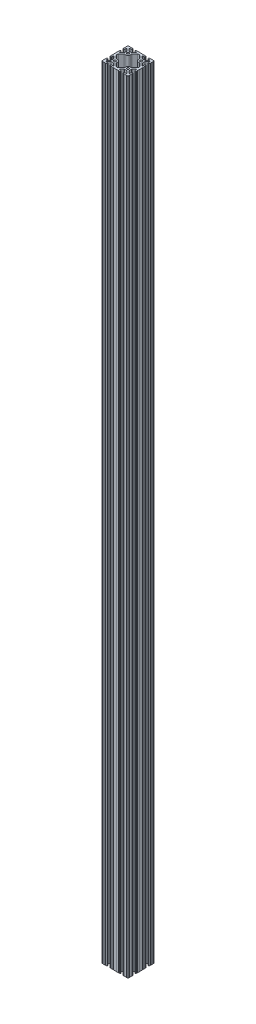
SolidWorks part; units mm, degrees
ref_plane "Piano frontale" through (0, 0, 0) normal (0, 0, 1) x (1, 0, 0)
ref_plane "Piano superiore" through (0, 0, 0) normal (0, 1, 0) x (1, 0, 0)
ref_plane "Piano destro" through (0, 0, 0) normal (1, 0, 0) x (0, 0, -1)
ref_plane "Piano1" through (0, 0, 0) normal (0, -1, 0) x (1, 0, 0)
sketch "Schizzo1" plane through (0, 0, 0) normal (0, -1, 0) x (1, 0, 0)
  line L0 (16.5037, -39.4963) -> (13.5247, -39.4963)
  line L1 (12.1105, -38.9105) -> (6.0284, -32.8284)
  line L2 (6.0284, -27.1716) -> (12.1105, -21.0895)
  line L3 (13.5247, -20.5037) -> (16.5037, -20.5037)
  line L4 (20.5037, -16.5037) -> (20.5037, -13.5247)
  line L5 (21.0895, -12.1105) -> (27.1716, -6.0284)
  line L6 (32.8284, -6.0284) -> (38.9105, -12.1105)
  line L7 (39.4963, -13.5247) -> (39.4963, -16.5037)
  line L8 (43.4963, -20.5037) -> (46.4753, -20.5037)
  line L9 (47.8895, -21.0895) -> (53.9716, -27.1716)
  line L10 (53.9716, -32.8284) -> (47.8895, -38.9105)
  line L11 (46.4753, -39.4963) -> (43.4963, -39.4963)
  line L12 (39.4963, -43.4963) -> (39.4963, -46.4753)
  line L13 (38.9105, -47.8895) -> (32.8284, -53.9716)
  line L14 (27.1716, -53.9716) -> (21.0895, -47.8895)
  line L15 (20.5037, -46.4753) -> (20.5037, -43.4963)
  line L16 (10.4, 0) -> (8.4, 0)
  line L17 (7.6, 0) -> (3, 0)
  line L18 (2.2, 0) -> (2, 0)
  line L19 (0, -2) -> (0, -2.2)
  line L20 (0, -3) -> (0, -7.6)
  line L21 (0, -8.4) -> (0, -10.4)
  line L22 (1.4, -11.8) -> (1.8, -11.8)
  line L23 (3.2, -10.4) -> (3.2, -7.3541)
  line L24 (4.5657, -6.7884) -> (8.9542, -11.177)
  line L25 (9.54, -12.5912) -> (9.54, -17.3716)
  line L26 (8.9542, -18.7858) -> (4.5657, -23.1743)
  line L27 (3.2, -22.6086) -> (3.2, -19.6)
  line L28 (1.8, -18.2) -> (1.4, -18.2)
  line L29 (0, -19.6) -> (0, -20.4)
  line L30 (0, -21.2) -> (0, -25.8)
  line L31 (0, -26.6) -> (0, -33.4)
  line L32 (0, -34.2) -> (0, -38.8)
  line L33 (0, -39.6) -> (0, -40.4)
  line L34 (1.4, -41.8) -> (1.8, -41.8)
  line L35 (3.2, -40.4) -> (3.2, -37.3914)
  line L36 (4.5657, -36.8257) -> (8.9542, -41.2142)
  line L37 (9.54, -42.6284) -> (9.54, -47.4088)
  line L38 (8.9542, -48.823) -> (4.5657, -53.2116)
  line L39 (3.2, -52.6459) -> (3.2, -49.6)
  line L40 (1.8, -48.2) -> (1.4, -48.2)
  line L41 (0, -49.6) -> (0, -51.6)
  line L42 (0, -52.4) -> (0, -57)
  line L43 (0, -57.8) -> (0, -58)
  line L44 (2, -60) -> (2.2, -60)
  line L45 (3, -60) -> (7.6, -60)
  line L46 (8.4, -60) -> (10.4, -60)
  line L47 (11.8, -58.6) -> (11.8, -58.2)
  line L48 (10.4, -56.8) -> (7.3541, -56.8)
  line L49 (6.7884, -55.4343) -> (11.177, -51.0458)
  line L50 (12.5912, -50.46) -> (17.3716, -50.46)
  line L51 (18.7858, -51.0458) -> (23.1743, -55.4343)
  line L52 (22.6086, -56.8) -> (19.6, -56.8)
  line L53 (18.2, -58.2) -> (18.2, -58.6)
  line L54 (19.6, -60) -> (20.4, -60)
  line L55 (21.2, -60) -> (25.8, -60)
  line L56 (26.6, -60) -> (33.4, -60)
  line L57 (34.2, -60) -> (38.8, -60)
  line L58 (39.6, -60) -> (40.4, -60)
  line L59 (41.8, -58.6) -> (41.8, -58.2)
  line L60 (40.4, -56.8) -> (37.3914, -56.8)
  line L61 (36.8257, -55.4343) -> (41.2142, -51.0458)
  line L62 (42.6284, -50.46) -> (47.4088, -50.46)
  line L63 (48.823, -51.0458) -> (53.2116, -55.4343)
  line L64 (52.6459, -56.8) -> (49.6, -56.8)
  line L65 (48.2, -58.2) -> (48.2, -58.6)
  line L66 (49.6, -60) -> (51.6, -60)
  line L67 (52.4, -60) -> (57, -60)
  line L68 (57.8, -60) -> (58, -60)
  line L69 (60, -58) -> (60, -57.8)
  line L70 (60, -57) -> (60, -52.4)
  line L71 (60, -51.6) -> (60, -49.6)
  line L72 (58.6, -48.2) -> (58.2, -48.2)
  line L73 (56.8, -49.6) -> (56.8, -52.6459)
  line L74 (55.4343, -53.2116) -> (51.0458, -48.823)
  line L75 (50.46, -47.4088) -> (50.46, -42.6284)
  line L76 (51.0458, -41.2142) -> (55.4343, -36.8257)
  line L77 (56.8, -37.3914) -> (56.8, -40.4)
  line L78 (58.2, -41.8) -> (58.6, -41.8)
  line L79 (60, -40.4) -> (60, -39.6)
  line L80 (60, -38.8) -> (60, -34.2)
  line L81 (60, -33.4) -> (60, -26.6)
  line L82 (60, -25.8) -> (60, -21.2)
  line L83 (60, -20.4) -> (60, -19.6)
  line L84 (58.6, -18.2) -> (58.2, -18.2)
  line L85 (56.8, -19.6) -> (56.8, -22.6086)
  line L86 (55.4343, -23.1743) -> (51.0458, -18.7858)
  line L87 (50.46, -17.3716) -> (50.46, -12.5912)
  line L88 (51.0458, -11.177) -> (55.4343, -6.7884)
  line L89 (56.8, -7.3541) -> (56.8, -10.4)
  line L90 (58.2, -11.8) -> (58.6, -11.8)
  line L91 (60, -10.4) -> (60, -8.4)
  line L92 (60, -7.6) -> (60, -3)
  line L93 (60, -2.2) -> (60, -2)
  line L94 (58, 0) -> (57.8, 0)
  line L95 (57, 0) -> (52.4, 0)
  line L96 (51.6, 0) -> (49.6, 0)
  line L97 (48.2, -1.4) -> (48.2, -1.8)
  line L98 (49.6, -3.2) -> (52.6459, -3.2)
  line L99 (53.2116, -4.5657) -> (48.823, -8.9542)
  line L100 (47.4088, -9.54) -> (42.6284, -9.54)
  line L101 (41.2142, -8.9542) -> (36.8257, -4.5657)
  line L102 (37.3914, -3.2) -> (40.4, -3.2)
  line L103 (41.8, -1.8) -> (41.8, -1.4)
  line L104 (40.4, 0) -> (39.6, 0)
  line L105 (38.8, 0) -> (34.2, 0)
  line L106 (33.4, 0) -> (26.6, 0)
  line L107 (25.8, 0) -> (21.2, 0)
  line L108 (20.4, 0) -> (19.6, 0)
  line L109 (18.2, -1.4) -> (18.2, -1.8)
  line L110 (19.6, -3.2) -> (22.6086, -3.2)
  line L111 (23.1743, -4.5657) -> (18.7858, -8.9542)
  line L112 (17.3716, -9.54) -> (12.5912, -9.54)
  line L113 (11.177, -8.9542) -> (6.7884, -4.5657)
  line L114 (7.3541, -3.2) -> (10.4, -3.2)
  line L115 (11.8, -1.8) -> (11.8, -1.4)
  arc A0 (13.5247, -39.4963) -> (12.1105, -38.9105) centre (13.5247, -37.4963) cw
  arc A1 (6.0284, -32.8284) -> (6.0284, -27.1716) centre (8.8569, -30) cw
  arc A2 (12.1105, -21.0895) -> (13.5247, -20.5037) centre (13.5247, -22.5037) cw
  arc A3 (16.5037, -20.5037) -> (20.5037, -16.5037) centre (16.5037, -16.5037) ccw
  arc A4 (20.5037, -13.5247) -> (21.0895, -12.1105) centre (22.5037, -13.5247) cw
  arc A5 (27.1716, -6.0284) -> (32.8284, -6.0284) centre (30, -8.8569) cw
  arc A6 (38.9105, -12.1105) -> (39.4963, -13.5247) centre (37.4963, -13.5247) cw
  arc A7 (39.4963, -16.5037) -> (43.4963, -20.5037) centre (43.4963, -16.5037) ccw
  arc A8 (46.4753, -20.5037) -> (47.8895, -21.0895) centre (46.4753, -22.5037) cw
  arc A9 (53.9716, -27.1716) -> (53.9716, -32.8284) centre (51.1431, -30) cw
  arc A10 (47.8895, -38.9105) -> (46.4753, -39.4963) centre (46.4753, -37.4963) cw
  arc A11 (43.4963, -39.4963) -> (39.4963, -43.4963) centre (43.4963, -43.4963) ccw
  arc A12 (39.4963, -46.4753) -> (38.9105, -47.8895) centre (37.4963, -46.4753) cw
  arc A13 (32.8284, -53.9716) -> (27.1716, -53.9716) centre (30, -51.1431) cw
  arc A14 (21.0895, -47.8895) -> (20.5037, -46.4753) centre (22.5037, -46.4753) cw
  arc A15 (20.5037, -43.4963) -> (16.5037, -39.4963) centre (16.5037, -43.4963) ccw
  circle A16 centre (15.0037, -15.0037) radius 2.62
  circle A17 centre (44.9963, -15.0037) radius 2.62
  circle A18 centre (44.9963, -44.9963) radius 2.62
  circle A19 centre (15.0037, -44.9963) radius 2.62
  arc A20 (11.8, -1.4) -> (10.4, 0) centre (10.4, -1.4) ccw
  arc A21 (8.4, 0) -> (7.6, 0) centre (8, 0) cw
  arc A22 (3, 0) -> (2.2, 0) centre (2.6, 0) cw
  arc A23 (2, 0) -> (0, -2) centre (2, -2) ccw
  arc A24 (0, -2.2) -> (0, -3) centre (0, -2.6) cw
  arc A25 (0, -7.6) -> (0, -8.4) centre (0, -8) cw
  arc A26 (0, -10.4) -> (1.4, -11.8) centre (1.4, -10.4) ccw
  arc A27 (1.8, -11.8) -> (3.2, -10.4) centre (1.8, -10.4) ccw
  arc A28 (3.2, -7.3541) -> (4.5657, -6.7884) centre (4, -7.3541) cw
  arc A29 (8.9542, -11.177) -> (9.54, -12.5912) centre (7.54, -12.5912) cw
  arc A30 (9.54, -17.3716) -> (8.9542, -18.7858) centre (7.54, -17.3716) cw
  arc A31 (4.5657, -23.1743) -> (3.2, -22.6086) centre (4, -22.6086) cw
  arc A32 (3.2, -19.6) -> (1.8, -18.2) centre (1.8, -19.6) ccw
  arc A33 (1.4, -18.2) -> (0, -19.6) centre (1.4, -19.6) ccw
  arc A34 (0, -20.4) -> (0, -21.2) centre (0, -20.8) cw
  arc A35 (0, -25.8) -> (0, -26.6) centre (0, -26.2) cw
  arc A36 (0, -33.4) -> (0, -34.2) centre (0, -33.8) cw
  arc A37 (0, -38.8) -> (0, -39.6) centre (0, -39.2) cw
  arc A38 (0, -40.4) -> (1.4, -41.8) centre (1.4, -40.4) ccw
  arc A39 (1.8, -41.8) -> (3.2, -40.4) centre (1.8, -40.4) ccw
  arc A40 (3.2, -37.3914) -> (4.5657, -36.8257) centre (4, -37.3914) cw
  arc A41 (8.9542, -41.2142) -> (9.54, -42.6284) centre (7.54, -42.6284) cw
  arc A42 (9.54, -47.4088) -> (8.9542, -48.823) centre (7.54, -47.4088) cw
  arc A43 (4.5657, -53.2116) -> (3.2, -52.6459) centre (4, -52.6459) cw
  arc A44 (3.2, -49.6) -> (1.8, -48.2) centre (1.8, -49.6) ccw
  arc A45 (1.4, -48.2) -> (0, -49.6) centre (1.4, -49.6) ccw
  arc A46 (0, -51.6) -> (0, -52.4) centre (0, -52) cw
  arc A47 (0, -57) -> (0, -57.8) centre (0, -57.4) cw
  arc A48 (0, -58) -> (2, -60) centre (2, -58) ccw
  arc A49 (2.2, -60) -> (3, -60) centre (2.6, -60) cw
  arc A50 (7.6, -60) -> (8.4, -60) centre (8, -60) cw
  arc A51 (10.4, -60) -> (11.8, -58.6) centre (10.4, -58.6) ccw
  arc A52 (11.8, -58.2) -> (10.4, -56.8) centre (10.4, -58.2) ccw
  arc A53 (7.3541, -56.8) -> (6.7884, -55.4343) centre (7.3541, -56) cw
  arc A54 (11.177, -51.0458) -> (12.5912, -50.46) centre (12.5912, -52.46) cw
  arc A55 (17.3716, -50.46) -> (18.7858, -51.0458) centre (17.3716, -52.46) cw
  arc A56 (23.1743, -55.4343) -> (22.6086, -56.8) centre (22.6086, -56) cw
  arc A57 (19.6, -56.8) -> (18.2, -58.2) centre (19.6, -58.2) ccw
  arc A58 (18.2, -58.6) -> (19.6, -60) centre (19.6, -58.6) ccw
  arc A59 (20.4, -60) -> (21.2, -60) centre (20.8, -60) cw
  arc A60 (25.8, -60) -> (26.6, -60) centre (26.2, -60) cw
  arc A61 (33.4, -60) -> (34.2, -60) centre (33.8, -60) cw
  arc A62 (38.8, -60) -> (39.6, -60) centre (39.2, -60) cw
  arc A63 (40.4, -60) -> (41.8, -58.6) centre (40.4, -58.6) ccw
  arc A64 (41.8, -58.2) -> (40.4, -56.8) centre (40.4, -58.2) ccw
  arc A65 (37.3914, -56.8) -> (36.8257, -55.4343) centre (37.3914, -56) cw
  arc A66 (41.2142, -51.0458) -> (42.6284, -50.46) centre (42.6284, -52.46) cw
  arc A67 (47.4088, -50.46) -> (48.823, -51.0458) centre (47.4088, -52.46) cw
  arc A68 (53.2116, -55.4343) -> (52.6459, -56.8) centre (52.6459, -56) cw
  arc A69 (49.6, -56.8) -> (48.2, -58.2) centre (49.6, -58.2) ccw
  arc A70 (48.2, -58.6) -> (49.6, -60) centre (49.6, -58.6) ccw
  arc A71 (51.6, -60) -> (52.4, -60) centre (52, -60) cw
  arc A72 (57, -60) -> (57.8, -60) centre (57.4, -60) cw
  arc A73 (58, -60) -> (60, -58) centre (58, -58) ccw
  arc A74 (60, -57.8) -> (60, -57) centre (60, -57.4) cw
  arc A75 (60, -52.4) -> (60, -51.6) centre (60, -52) cw
  arc A76 (60, -49.6) -> (58.6, -48.2) centre (58.6, -49.6) ccw
  arc A77 (58.2, -48.2) -> (56.8, -49.6) centre (58.2, -49.6) ccw
  arc A78 (56.8, -52.6459) -> (55.4343, -53.2116) centre (56, -52.6459) cw
  arc A79 (51.0458, -48.823) -> (50.46, -47.4088) centre (52.46, -47.4088) cw
  arc A80 (50.46, -42.6284) -> (51.0458, -41.2142) centre (52.46, -42.6284) cw
  arc A81 (55.4343, -36.8257) -> (56.8, -37.3914) centre (56, -37.3914) cw
  arc A82 (56.8, -40.4) -> (58.2, -41.8) centre (58.2, -40.4) ccw
  arc A83 (58.6, -41.8) -> (60, -40.4) centre (58.6, -40.4) ccw
  arc A84 (60, -39.6) -> (60, -38.8) centre (60, -39.2) cw
  arc A85 (60, -34.2) -> (60, -33.4) centre (60, -33.8) cw
  arc A86 (60, -26.6) -> (60, -25.8) centre (60, -26.2) cw
  arc A87 (60, -21.2) -> (60, -20.4) centre (60, -20.8) cw
  arc A88 (60, -19.6) -> (58.6, -18.2) centre (58.6, -19.6) ccw
  arc A89 (58.2, -18.2) -> (56.8, -19.6) centre (58.2, -19.6) ccw
  arc A90 (56.8, -22.6086) -> (55.4343, -23.1743) centre (56, -22.6086) cw
  arc A91 (51.0458, -18.7858) -> (50.46, -17.3716) centre (52.46, -17.3716) cw
  arc A92 (50.46, -12.5912) -> (51.0458, -11.177) centre (52.46, -12.5912) cw
  arc A93 (55.4343, -6.7884) -> (56.8, -7.3541) centre (56, -7.3541) cw
  arc A94 (56.8, -10.4) -> (58.2, -11.8) centre (58.2, -10.4) ccw
  arc A95 (58.6, -11.8) -> (60, -10.4) centre (58.6, -10.4) ccw
  arc A96 (60, -8.4) -> (60, -7.6) centre (60, -8) cw
  arc A97 (60, -3) -> (60, -2.2) centre (60, -2.6) cw
  arc A98 (60, -2) -> (58, 0) centre (58, -2) ccw
  arc A99 (57.8, 0) -> (57, 0) centre (57.4, 0) cw
  arc A100 (52.4, 0) -> (51.6, 0) centre (52, 0) cw
  arc A101 (49.6, 0) -> (48.2, -1.4) centre (49.6, -1.4) ccw
  arc A102 (48.2, -1.8) -> (49.6, -3.2) centre (49.6, -1.8) ccw
  arc A103 (52.6459, -3.2) -> (53.2116, -4.5657) centre (52.6459, -4) cw
  arc A104 (48.823, -8.9542) -> (47.4088, -9.54) centre (47.4088, -7.54) cw
  arc A105 (42.6284, -9.54) -> (41.2142, -8.9542) centre (42.6284, -7.54) cw
  arc A106 (36.8257, -4.5657) -> (37.3914, -3.2) centre (37.3914, -4) cw
  arc A107 (40.4, -3.2) -> (41.8, -1.8) centre (40.4, -1.8) ccw
  arc A108 (41.8, -1.4) -> (40.4, 0) centre (40.4, -1.4) ccw
  arc A109 (39.6, 0) -> (38.8, 0) centre (39.2, 0) cw
  arc A110 (34.2, 0) -> (33.4, 0) centre (33.8, 0) cw
  arc A111 (26.6, 0) -> (25.8, 0) centre (26.2, 0) cw
  arc A112 (21.2, 0) -> (20.4, 0) centre (20.8, 0) cw
  arc A113 (19.6, 0) -> (18.2, -1.4) centre (19.6, -1.4) ccw
  arc A114 (18.2, -1.8) -> (19.6, -3.2) centre (19.6, -1.8) ccw
  arc A115 (22.6086, -3.2) -> (23.1743, -4.5657) centre (22.6086, -4) cw
  arc A116 (18.7858, -8.9542) -> (17.3716, -9.54) centre (17.3716, -7.54) cw
  arc A117 (12.5912, -9.54) -> (11.177, -8.9542) centre (12.5912, -7.54) cw
  arc A118 (6.7884, -4.5657) -> (7.3541, -3.2) centre (7.3541, -4) cw
  arc A119 (10.4, -3.2) -> (11.8, -1.8) centre (10.4, -1.8) ccw
  dimension "D1" = 60
  dimension "D2" = 60
extrude "Estrusione-Estrusione1" add sketch "Schizzo1" against normal blind 1780
